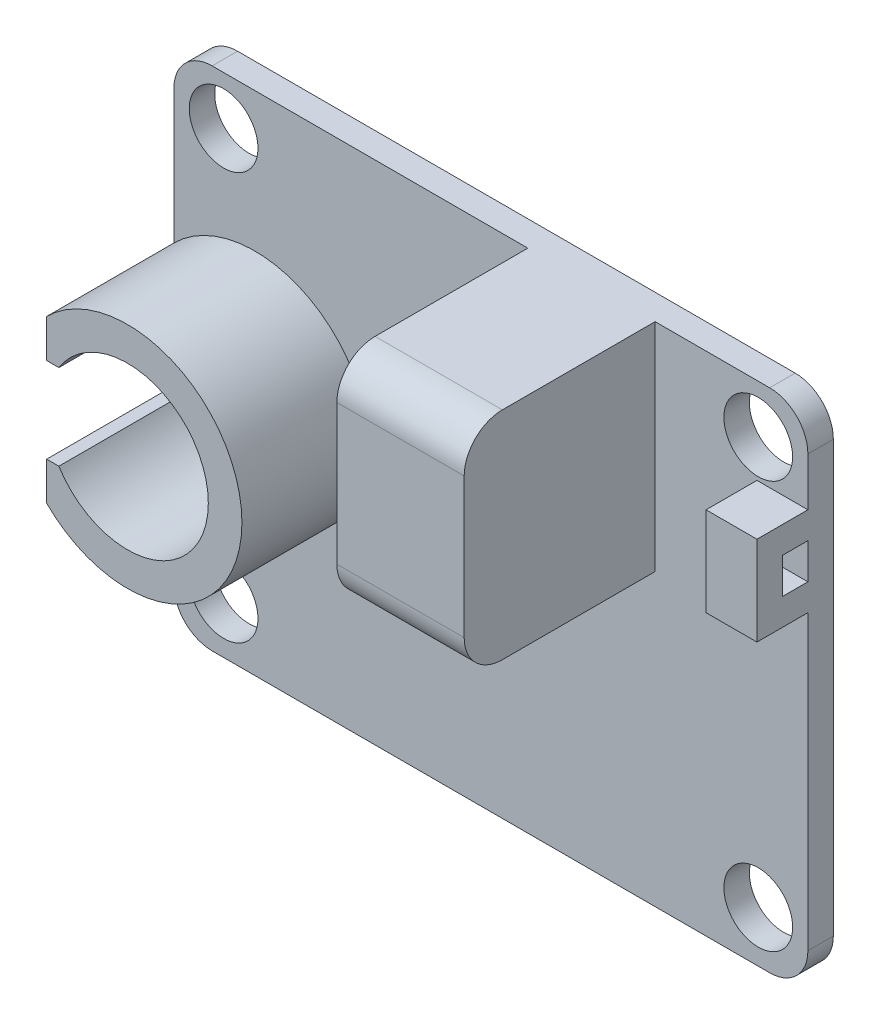
SolidWorks part; units mm, degrees
ref_plane "Alzado" through (0, 0, 0) normal (0, 0, 1) x (1, 0, 0)
ref_plane "Planta" through (0, 0, 0) normal (0, 1, 0) x (1, 0, 0)
ref_plane "Vista lateral" through (0, 0, 0) normal (1, 0, 0) x (0, 0, -1)
sketch "Croquis1" plane through (0, 0, 0) normal (0, 0, 1) x (1, 0, 0)
  line L1 (-56.8634, 16.1421) -> (-7.0634, 16.1421)
  line L2 (-56.8634, 16.1421) -> (-56.8634, -23.6579)
  line L3 (-56.8634, -23.6579) -> (-7.0634, -23.6579)
  line L4 (-7.0634, 16.1421) -> (-7.0634, -23.6579)
  circle A0 centre (-52.9634, 12.3421) radius 2.7
  circle A1 centre (-10.9634, 12.3421) radius 2.7
  circle A2 centre (-10.9634, -19.6579) radius 2.7
  circle A3 centre (-52.9634, -19.6579) radius 2.7
  dimension "D3" = 3.8
  dimension "D7" = 5.4
  dimension "D1" = 49.8
  dimension "D2" = 39.8
  dimension "D4" = 3.9
  dimension "D5" = 2
  dimension "D6" = 2
extrude "Saliente-Extruir1" add sketch "Croquis1" along normal blind 6
sketch "Croquis2" plane through (0, 0, 6) normal (0, 0, 1) x (1, 0, 0)
  line L0 (-56.8634, -23.6579) -> (-7.0634, 16.1421) construction
  line L2 (-49.9634, -16.7579) -> (-13.9634, -16.7579)
  line L3 (-51.9634, -14.7579) -> (-51.9634, 7.2421)
  line L4 (-49.9634, 9.2421) -> (-13.9634, 9.2421)
  line L5 (-11.9634, -14.7579) -> (-11.9634, 7.2421)
  line L6 (-51.9634, -16.7579) -> (-11.9634, 9.2421) construction
  line L7 (-51.9634, 9.2421) -> (-11.9634, -16.7579) construction
  arc A0 (-11.9634, 7.2421) -> (-13.9634, 9.2421) centre (-13.9634, 7.2421) ccw
  arc A1 (-11.9634, -14.7579) -> (-13.9634, -16.7579) centre (-13.9634, -14.7579) cw
  arc A2 (-49.9634, -16.7579) -> (-51.9634, -14.7579) centre (-49.9634, -14.7579) cw
  arc A3 (-49.9634, 9.2421) -> (-51.9634, 7.2421) centre (-49.9634, 7.2421) ccw
  point P4 (-31.9634, -3.7579)
  dimension "D3" = 2
  dimension "D1" = 40
  dimension "D2" = 26
extrude "Cortar-Extruir1" cut sketch "Croquis2" against normal blind 4
fillet "Redondeo1" radius 3 4 edges at (-56.8634, 16.1421, 3) (-7.0634, 16.1421, 3) (-7.0634, -23.6579, 3) (-56.8634, -23.6579, 3)
sketch "Croquis4" plane through (0, 0, 0) normal (0, 0, -1) x (-1, 0, 0)
  line L1 (56.8634, 13.1421) -> (56.8634, -20.6579) construction
  line L2 (56.8634, 4.2421) -> (61.8634, 4.2421)
  line L4 (61.8634, -11.7579) -> (56.8634, -11.7579)
  line L6 (56.8634, 4.2421) -> (61.8634, -11.7579) construction
  line L7 (57.8634, -0.2579) -> (61.8634, -0.2579)
  line L8 (57.8634, -7.2579) -> (61.8634, -7.2579)
  line L9 (61.8634, 4.2421) -> (61.8634, -0.2579)
  line L10 (61.8634, -7.2579) -> (61.8634, -11.7579)
  line L11 (56.8634, 4.2421) -> (56.8634, -0.4038)
  line L12 (56.8634, -7.112) -> (56.8634, -11.7579)
  arc A2 (57.8634, -0.2579) -> (56.8634, -0.4038) centre (57.8634, -3.7579) ccw
  arc A3 (57.8634, -7.2579) -> (56.8634, -7.112) centre (57.8634, -3.7579) cw
  dimension "D1" = 5
  dimension "D2" = 3.5
  dimension "D3" = 5
extrude "Saliente-Extruir3" add sketch "Croquis4" against normal blind 3
sketch "Croquis5" plane through (0, 0, 3) normal (0, 0, 1) x (1, 0, 0)
  circle A1 centre (-57.8634, -3.7579) radius 6.35
extrude "Cortar-Extruir2" cut sketch "Croquis5" along normal up to vertex (3 mm away)
sketch "Croquis6" plane through (0, 0, 3) normal (0, 0, 1) x (1, 0, 0)
  line L6 (-61.8634, 4.2421) -> (-51.9634, 4.2421)
  line L8 (-51.9634, -11.7579) -> (-61.8634, -11.7579)
  line L9 (-61.8634, 4.2421) -> (-61.8634, 1.1739)
  line L10 (-61.8634, -0.2579) -> (-61.8634, 4.2421) construction
  line L11 (-61.8634, -11.7579) -> (-61.8634, -8.6897)
  line L12 (-51.9634, 4.2421) -> (-48.9634, 4.2421)
  line L13 (-48.9634, 4.2421) -> (-48.9634, -11.7579)
  line L14 (-48.9634, -11.7579) -> (-51.9634, -11.7579)
  arc A5 (-61.8634, 1.1739) -> (-61.8634, -8.6897) centre (-57.8634, -3.7579) cw
extrude "Saliente-Extruir4" add sketch "Croquis6" along normal blind 10
sketch "Croquis7" plane through (0, 0, 2) normal (0, 0, 1) x (1, 0, 0)
  line L0 (-51.9634, -3.7579) -> (-51.9634, 4.2421)
  line L1 (-51.9634, 7.2421) -> (-51.9634, -14.7579) construction
  line L2 (-51.9634, 4.2421) -> (-48.9634, 4.2421)
  line L3 (-48.9634, 4.2421) -> (-48.9634, -11.7579)
  line L4 (-48.9634, -11.7579) -> (-51.9634, -11.7579)
  line L5 (-51.9634, -11.7579) -> (-51.9634, -3.7579)
extrude "Saliente-Extruir5" add sketch "Croquis7" along normal blind 2
sketch "Croquis8" plane through (0, 0, 3) normal (0, 0, 1) x (1, 0, 0)
  line L0 (-56.8634, -0.4038) -> (-56.8634, -7.112)
  arc A0 (-56.8634, -0.4038) -> (-56.8634, -7.112) centre (-56.8634, -3.7579) cw
extrude "Cortar-Extruir3" cut sketch "Croquis8" against normal up to vertex
sketch "Croquis9" plane through (0, 0, 6) normal (0, 0, 1) x (1, 0, 0)
  line L0 (-56.8634, -11.7579) -> (-56.8634, -27.4922)
  line L1 (-56.8634, -27.4922) -> (-1.8171, -27.4922)
  line L2 (-1.8171, -27.4922) -> (-1.8171, 22.8618)
  line L3 (-1.8171, 22.8618) -> (-56.8634, 22.8618)
  line L4 (-56.8634, 22.8618) -> (-56.8634, 4.2421)
  line L5 (-56.8634, 4.2421) -> (-47.1727, 4.2421)
  line L6 (-47.1727, 4.2421) -> (-47.1727, -11.7579)
  line L7 (-47.1727, -11.7579) -> (-56.8634, -11.7579)
extrude "Cortar-Extruir4" cut sketch "Croquis9" against normal blind 4
sketch "Croquis10" plane through (0, 0, 2) normal (0, 0, 1) x (1, 0, 0)
  line L0 (-7.0634, -20.6579) -> (-7.0634, 13.1421) construction
  line L1 (-7.0634, 9.3421) -> (-11.0634, 9.3421)
  line L2 (-7.0634, 9.3421) -> (-7.0634, 2.3421)
  line L3 (-7.0634, 2.3421) -> (-11.0634, 2.3421)
  line L4 (-11.0634, 9.3421) -> (-11.0634, 2.3421)
  circle A0 centre (-10.9634, 12.3421) radius 2.7 construction
  point P6 (-9.0634, 9.3421)
  dimension "D1" = 7
  dimension "D2" = 3
  dimension "D3" = 4
extrude "Saliente-Extruir6" add sketch "Croquis10" along normal blind 4
sketch "Croquis11" plane through (-7.0634, 0, 0) normal (1, 0, 0) x (0, 0, -1)
  line L0 (-6, 5.8421) -> (-2, 5.8421) construction
  line L1 (-6, 2.3421) -> (-6, 9.3421) construction
  line L2 (-2, 5.8421) -> (-2, 7.2421)
  line L3 (-2, 7.2421) -> (-4, 7.2421)
  line L4 (-4, 7.2421) -> (-4, 4.4421)
  line L5 (-4, 4.4421) -> (-2, 4.4421)
  line L6 (-2, 4.4421) -> (-2, 5.8421)
  dimension "D1" = 1.4
  dimension "D2" = 1.4
extrude "Cortar-Extruir5" cut sketch "Croquis11" against normal up to vertex (4 mm away)
ref_plane "Plano2" through (-48.9634, 4.2421, 13) normal (0, 1, 0) x (1, 0, 0)
sketch "Croquis16" plane through (0, 0, 2) normal (0, 0, 1) x (1, 0, 0)
  line L1 (-64.1981, 16.945) -> (-35.2393, 16.945)
  line L2 (-64.1981, 16.945) -> (-64.1981, -30.9257)
  line L3 (-64.1981, -30.9257) -> (-35.2393, -30.9257)
  line L4 (-35.2393, 16.945) -> (-35.2393, -30.9257)
extrude "Cortar-Extruir6" cut sketch "Croquis16" along normal up to vertex (2 mm away)
sketch "Croquis17" plane through (0, 0, 2) normal (0, 0, 1) x (1, 0, 0)
  line L1 (-61.8634, 4.2421) -> (-56.8634, 4.2421)
  line L2 (-61.8634, 4.2421) -> (-61.8634, -11.7579)
  line L3 (-61.8634, -11.7579) -> (-56.8634, -11.7579)
  line L4 (-56.8634, 4.2421) -> (-56.8634, -11.7579)
extrude "Cortar-Extruir7" cut sketch "Croquis17" against normal blind 10
sketch "Croquis18" plane through (0, 0, 2) normal (0, 0, 1) x (1, 0, 0)
  line L0 (-56.8634, -0.4038) -> (-50.5134, -0.4038)
  line L1 (-56.8634, -7.112) -> (-50.5134, -7.112)
  line L2 (-56.8634, -0.4038) -> (-56.8634, -7.112)
  arc A0 (-50.5134, -0.4038) -> (-50.5134, -7.112) centre (-50.5134, -3.7579) cw
extrude "Cortar-Extruir8" cut sketch "Croquis18" against normal up to vertex (2 mm away)
sketch "Croquis19" plane through (0, 0, 2) normal (0, 0, 1) x (1, 0, 0)
  line L0 (-55.9053, -0.4038) -> (-56.8634, -0.4038)
  line L1 (-50.5134, -0.4038) -> (-56.8634, -0.4038) construction
  line L2 (-56.8634, -0.4038) -> (-56.8634, 2.5962)
  line L3 (-56.8634, 13.1421) -> (-56.8634, -0.4038) construction
  line L4 (-55.9053, -7.112) -> (-56.8634, -7.112)
  line L5 (-56.8634, -7.112) -> (-50.5134, -7.112) construction
  line L6 (-56.8634, -7.112) -> (-56.8634, -10.112)
  line L7 (-56.8634, -7.112) -> (-56.8634, -20.6579) construction
  circle A0 centre (-50.5134, -3.7579) radius 6.35
  arc A1 (-56.8634, 2.5962) -> (-56.8634, -10.112) centre (-50.5093, -3.7579) cw
  line M4 (-56.8634, -0.4038) -> (-50.5134, -0.4038)
  line M6 (-50.5134, -7.112) -> (-56.8634, -7.112)
  line M7 (-56.8634, -7.112) -> (-56.8634, -20.6579)
  line M23 (-56.8634, 13.1421) -> (-56.8634, -0.4038)
  dimension "D1" = 3
extrude "Saliente-Extruir7" add sketch "Croquis19" along normal blind 10 contours A1 A0 M23 M4 M6 M7
sketch "Croquis21" plane through (0, 0, 2) normal (0, 0, 1) x (1, 0, 0)
  line L0 (-10.0634, 16.1421) -> (-53.8634, 16.1421) construction
  line L1 (-19.0634, 16.1421) -> (-29.0634, 16.1421)
  line L2 (-19.0634, 16.1421) -> (-19.0634, -0.8579)
  line L3 (-19.0634, -0.8579) -> (-29.0634, -0.8579)
  line L4 (-29.0634, 16.1421) -> (-29.0634, -0.8579)
  line L5 (-29.0634, 7.6421) -> (-45.8481, 7.6421) construction
  line L6 (-41.5233, -3.7579) -> (-41.5233, 7.6421) construction
  line L7 (-7.0634, -20.6579) -> (-7.0634, 2.3421) construction
  arc A0 (-56.8634, -10.112) -> (-56.8634, 2.5962) centre (-50.5093, -3.7579) ccw construction
  dimension "D1" = 17
  dimension "D2" = 12
  dimension "D3" = 10
extrude "Saliente-Extruir8" add sketch "Croquis21" along normal blind 15
sketch "Croquis22" plane through (-29.0634, 0, 0) normal (-1, 0, 0) x (0, 0, 1)
  line L0 (17, 7.6421) -> (2, 7.6421) construction
  line L1 (17, 16.1421) -> (17, -0.8579) construction
  line L2 (2, 16.1421) -> (2, -0.8579) construction
  circle A0 centre (9, 7.6421) radius 7
  dimension "D1" = 7
extrude "Cortar-Extruir9" cut sketch "Croquis22" against normal blind 8
fillet "Redondeo2" radius 3 2 edges at (-24.0634, -0.8579, 17) (-24.0634, 16.1421, 17)
